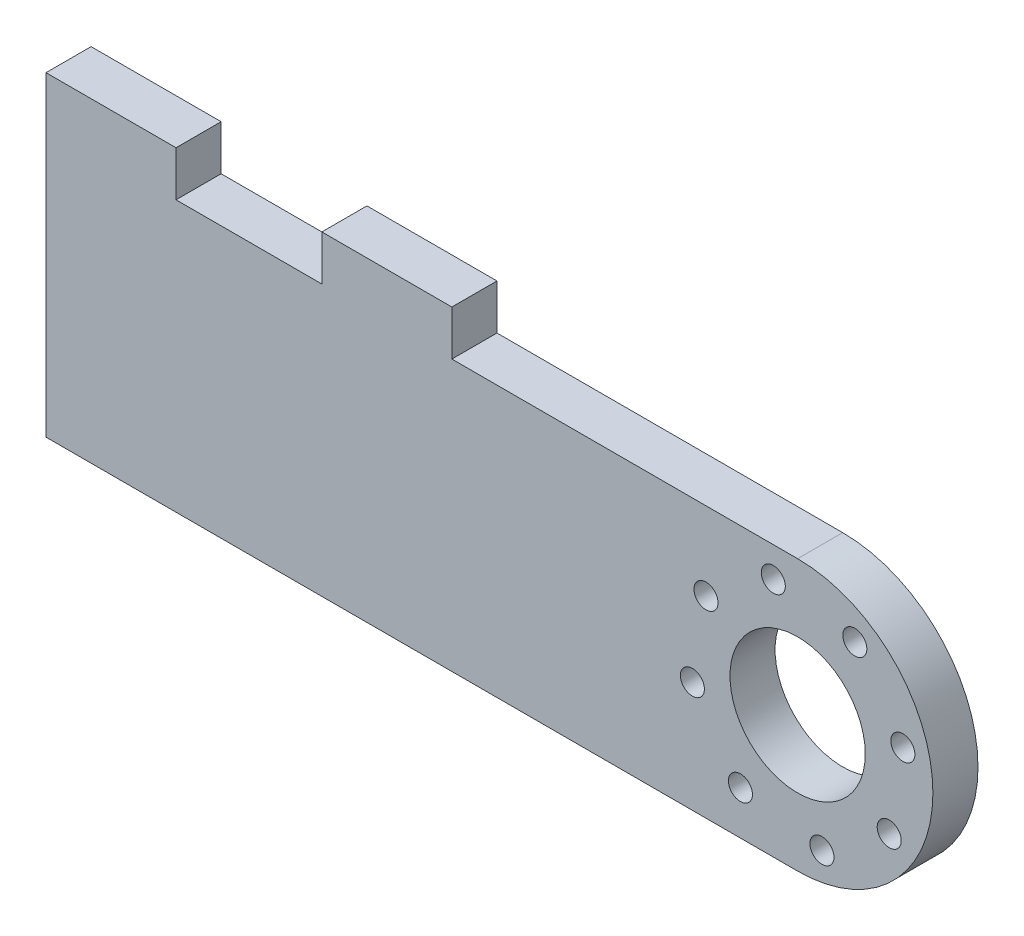
SolidWorks part; units mm, degrees
ref_plane "Plan de face" through (0, 0, 0) normal (0, 0, 1) x (1, 0, 0)
ref_plane "Plan de dessus" through (0, 0, 0) normal (0, 1, 0) x (1, 0, 0)
ref_plane "Plan de droite" through (0, 0, 0) normal (1, 0, 0) x (0, 0, -1)
sketch "Esquisse1" plane through (0, 0, 0) normal (0, 0, 1) x (1, 0, 0)
  line L5 (1.5978, 9) -> (24.5978, 9)
  line L12 (24.5978, 0) -> (22.9791, 7) construction
  line L13 (24.5978, 0) -> (28.4029, 6.0944) construction
  line L14 (1.5978, 9) -> (1.5978, 12)
  line L16 (-25.4022, 12) -> (-25.4022, -9)
  line L17 (-25.4022, -9) -> (24.5978, -9)
  line L18 (1.5978, 12) -> (-7.0522, 12)
  line L19 (-7.0522, 12) -> (-7.0522, 9)
  line L20 (-7.0522, 9) -> (-16.7522, 9)
  line L21 (-16.7522, 9) -> (-16.7522, 12)
  line L22 (-16.7522, 12) -> (-25.4022, 12)
  arc A1 (24.5978, 9) -> (24.5978, -9) centre (24.5978, 0) cw
  circle A2 centre (24.5978, 0) radius 4.5
  circle A11 centre (22.9791, 7) radius 0.8
  circle A12 centre (28.4029, 6.0944) radius 0.8
  circle A13 centre (31.5978, 1.6188) radius 0.8
  circle A14 centre (30.6922, -3.8051) radius 0.8
  circle A15 centre (26.2166, -7) radius 0.8
  circle A16 centre (20.7927, -6.0944) radius 0.8
  circle A17 centre (17.5978, -1.6188) radius 0.8
  circle A18 centre (18.5034, 3.8051) radius 0.8
  dimension "D1" = 9.7
  dimension "D4" = 9
  dimension "D5" = 9
  dimension "D6" = 1.6
  dimension "D10" = 8.65
  dimension "D11" = 8.65
  dimension "D2" = 3
  dimension "D3" = 3
  dimension "D7" = 7
  dimension "D9" = 45
  dimension "D12" = 50
  dimension "D8" = 8
extrude "Boss.-Extru.1" add sketch "Esquisse1" along normal blind 3
